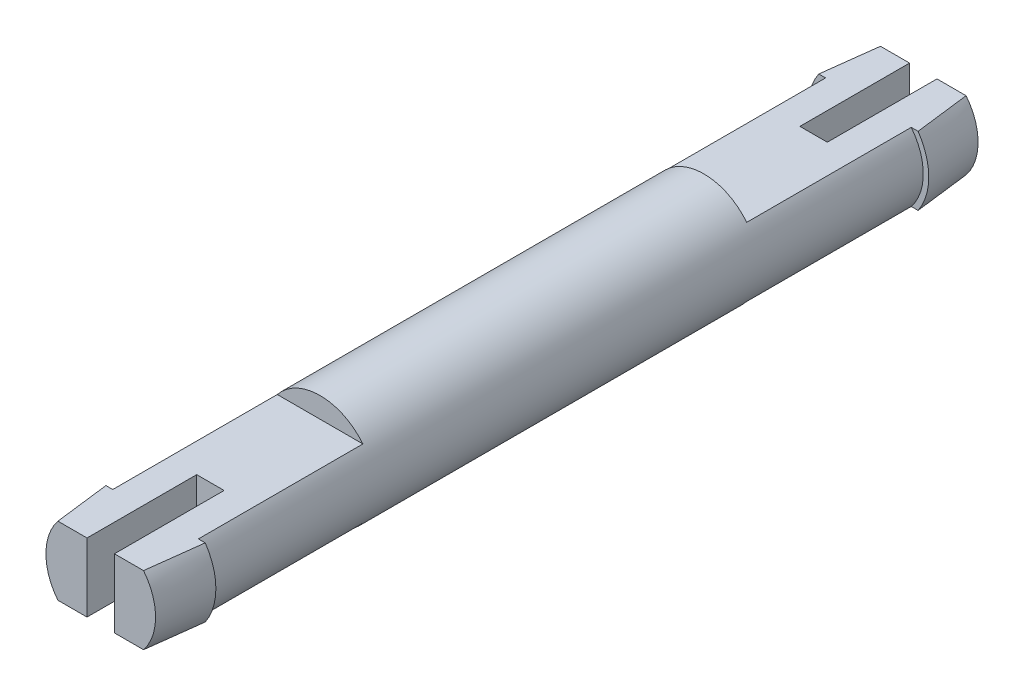
SolidWorks part; units mm, degrees
ref_plane "前视基准面" through (0, 0, 0) normal (0, 0, 1) x (1, 0, 0)
ref_plane "上视基准面" through (0, 0, 0) normal (0, 1, 0) x (1, 0, 0)
ref_plane "右视基准面" through (0, 0, 0) normal (1, 0, 0) x (0, 0, -1)
sketch "草图1" plane through (0, 0, 0) normal (0, 0, 1) x (1, 0, 0)
  circle A0 centre (0, 0) radius 2
extrude "凸台-拉伸1" add sketch "草图1" against normal blind 30
sketch "草图2" plane through (0, 0, 0) normal (0, 1, 0) x (1, 0, 0)
  line L0 (0, 0) -> (0, 2)
  line L1 (0, 2) -> (2.2, 2)
  line L2 (0, 0) -> (2, 0)
  line L3 (2, 0) -> (2.2, 2)
  dimension "D1" = 2.2
  dimension "D2" = 2
revolve "旋转1" add sketch "草图2" angle 360 about L0
sketch "草图3" plane through (0, 0, 0) normal (0, 0, 1) x (1, 0, 0)
  line L0 (-2.1, 1.25) -> (-2.1, 2.25)
  line L1 (-2.1, 1.25) -> (2.1, 1.25)
  line L2 (2.1, 1.25) -> (2.1, 2.25)
  line L3 (-2.1, -1.25) -> (2.1, -1.25)
  line L5 (-2.1, -2.25) -> (2.1, -2.25)
  line L6 (-2.1, -2.25) -> (-2.1, -1.25)
  line L7 (-2.1, 2.25) -> (2.1, 2.25)
  line L8 (2.1, -2.25) -> (2.1, -1.25)
  dimension "D1" = 1.25
  dimension "D2" = 1.25
  dimension "D3" = 1
  dimension "D4" = 1
extrude "切除-拉伸1" cut sketch "草图3" against normal blind 8
sketch "草图4" plane through (0, -1.25, 0) normal (0, -1, 0) x (1, 0, 0)
  line L0 (1.5612, 0) -> (-1.5612, 0) construction
  line L1 (-0.5, 0) -> (0.5, 0)
  line L2 (-0.5, 0) -> (-0.5, -4)
  line L3 (-0.5, -4) -> (0.5, -4)
  line L4 (0.5, 0) -> (0.5, -4)
extrude "切除-拉伸2" cut sketch "草图4" against normal up to next
sketch "草图5" plane through (0, 0, 0) normal (0, 1, 0) x (1, 0, 0)
  line L0 (0, 30) -> (0, 28)
  line L1 (2, 30) -> (-2, 30) construction
  line L2 (0, 28) -> (2.2, 28)
  line L3 (2.2, 28) -> (2, 30)
  line L4 (2, 30) -> (0, 30)
  line L5 (0, 58.1377) -> (0, 60.3241) construction
  dimension "D1" = 2.2
  dimension "D2" = 2
revolve "旋转2" add sketch "草图5" angle 360 about L5
sketch "草图6" plane through (0, 0, -30) normal (0, 0, -1) x (-1, 0, 0)
  line L1 (-2.1, 1.25) -> (2.1, 1.25)
  line L2 (-2.1, 1.25) -> (-2.1, 2.25)
  line L3 (-2.1, 2.25) -> (2.1, 2.25)
  line L4 (2.1, 1.25) -> (2.1, 2.25)
  line L5 (-2.1, -1.25) -> (2.1, -1.25)
  line L6 (-2.1, -1.25) -> (-2.1, -2.25)
  line L7 (-2.1, -2.25) -> (2.1, -2.25)
  line L8 (2.1, -1.25) -> (2.1, -2.25)
  dimension "D1" = 1.25
  dimension "D2" = 1.25
  dimension "D3" = 1
  dimension "D4" = 1
extrude "切除-拉伸3" cut sketch "草图6" against normal blind 8
sketch "草图7" plane through (0, 1.25, 0) normal (0, 1, 0) x (1, 0, 0)
  line L0 (0, 30) -> (0, 26) construction
  line L1 (-1.5612, 30) -> (1.5612, 30) construction
  line L2 (-0.5, 26) -> (0.5, 26)
  line L3 (0.5, 26) -> (0.5, 30)
  line L4 (0.5, 30) -> (-0.5, 30)
  line L5 (-0.5, 26) -> (-0.5, 30)
  dimension "D1" = 4
  dimension "D2" = 0.5
extrude "切除-拉伸4" cut sketch "草图7" against normal through all
